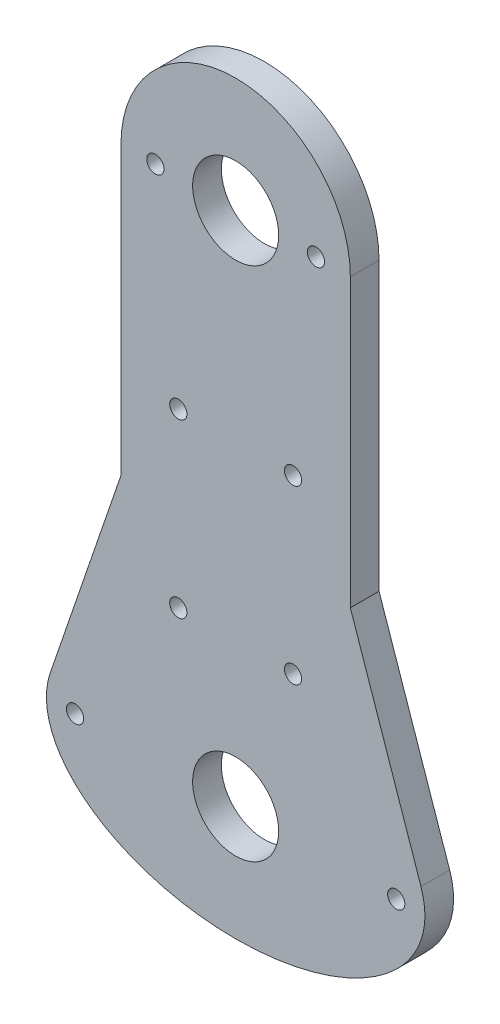
SolidWorks part; units mm, degrees
ref_plane "前视基准面" through (0, 0, 0) normal (0, 0, 1) x (1, 0, 0)
ref_plane "上视基准面" through (0, 0, 0) normal (0, 1, 0) x (1, 0, 0)
ref_plane "右视基准面" through (0, 0, 0) normal (1, 0, 0) x (0, 0, -1)
sketch "草图1" plane through (0, 0, 0) normal (0, 0, 1) x (1, 0, 0)
  line L0 (-20, -50) -> (-32.3109, -85.934)
  line L1 (-20, 0) -> (20, 0)
  line L2 (-20, 0) -> (-20, -90)
  line L3 (-20, -90) -> (20, -90)
  line L4 (20, 0) -> (20, -90)
  line L5 (-20, -50) -> (20, -50) construction
  line L6 (0, -50) -> (0, -154.1436) construction
  line L7 (20, -50) -> (32.3109, -85.934)
  circle A0 centre (0, 0) radius 20
  circle A1 centre (0, -90) radius 20
  ellipse E0 centre (0, -90) end of major axis (-33, -90) minor radius 20
  point P19 (0, 0)
  dimension "D1" = 40
  dimension "D2" = 90
  dimension "D3" = 40
  dimension "D4" = 33
extrude "凸台-拉伸1" add sketch "草图1" along normal blind 5 contours E0 L4 A0 L2 | E0 L2 L0 | L2 E0 A1 | A1 E0 L2 | L4 E0 A1 | E0 L7 L4 | E0 L4 A1 | L1 A0 | L1 A0 | L3 A1 | L3 A1
sketch "草图3" plane through (0, 0, 5) normal (0, 0, 1) x (1, 0, 0)
  line L4 (32.3109, -85.934) -> (20, -50)
  line L5 (20, -50) -> (20, 0)
  line L6 (-20, 0) -> (-20, -50)
  line L7 (-20, -50) -> (-32.3109, -85.934)
  line L8 (32.3109, -85.934) -> (20, -50)
  line L9 (20, -50) -> (20, 0)
  line L10 (-20, 0) -> (-20, -50)
  line L11 (-20, -50) -> (-32.3109, -85.934)
  circle A0 centre (0, -90) radius 7.5
  arc A1 (20, 0) -> (-20, 0) centre (0, 0) ccw
  arc A2 (20, 0) -> (-20, 0) centre (0, 0) ccw
  ellipse E1 centre (0, -90) end of major axis (-33, -90) minor radius 20 (-32.3109, -85.934) -> (32.3109, -85.934) ccw
  ellipse E2 centre (0, -90) end of major axis (-33, -90) minor radius 20 (-32.3109, -85.934) -> (32.3109, -85.934) ccw
  dimension "D2" = 15
  dimension "D1" = 0
extrude "切除-拉伸2" cut sketch "草图3" against normal through all both and the other way through all flip side to cut
sketch "草图4" plane through (0, 0, 5) normal (0, 0, 1) x (1, 0, 0)
  circle A0 centre (0, 0) radius 7.5
  dimension "D1" = 15
extrude "切除-拉伸3" cut sketch "草图4" against normal through all
sketch "草图5" plane through (0, 0, 5) normal (0, 0, 1) x (1, 0, 0)
  line L0 (0, -90) -> (33, -90) construction
  line L1 (0, -70) -> (0, -90) construction
  line L2 (0, 0) -> (0, -70) construction
  line L3 (0, -35) -> (20, -35) construction
  line L4 (32.3109, -85.934) -> (20, -50)
  line L5 (20, -50) -> (20, 0)
  line L6 (-20, 0) -> (-20, -50)
  line L7 (-20, -50) -> (-32.3109, -85.934)
  line L8 (32.3109, -85.934) -> (20, -50) construction
  line L9 (20, -50) -> (20, 0) construction
  line L10 (-20, 0) -> (-20, -50) construction
  line L11 (-20, -50) -> (-32.3109, -85.934) construction
  line L12 (10, -35) -> (10, -65) construction
  line L13 (10, -35) -> (10, 0) construction
  line L14 (10, -17.5) -> (0, -17.5) construction
  line L15 (10, 0) -> (14, 0) construction
  line L16 (0, -90) -> (0, -97.5) construction
  line L17 (0, -97.5) -> (0, -110) construction
  circle A0 centre (28, -90) radius 1.5
  arc A1 (20, 0) -> (-20, 0) centre (0, 0) ccw
  arc A2 (20, 0) -> (-20, 0) centre (0, 0) ccw construction
  circle A3 centre (14, 0) radius 1.5
  circle A5 centre (10, -35) radius 1.5
  circle A6 centre (10, -65) radius 1.5
  circle A7 centre (-14, 0) radius 1.5
  circle A8 centre (-10, -35) radius 1.5
  circle A9 centre (-10, -65) radius 1.5
  circle A10 centre (-28, -90) radius 1.5
  circle A11 centre (0, -90) radius 7.5 construction
  ellipse E1 centre (0, -90) end of major axis (-33, -90) minor radius 20 (-32.3109, -85.934) -> (32.3109, -85.934) ccw
  ellipse E2 centre (0, -90) end of major axis (-33, -90) minor radius 20 (-32.3109, -85.934) -> (32.3109, -85.934) ccw construction
  dimension "D3" = 3
  dimension "D6" = 3
  dimension "D7" = 3
  dimension "D8" = 3
  dimension "D2" = 5
  dimension "D4" = 30
  dimension "D5" = 4
  dimension "D1" = 0
extrude "切除-拉伸4" cut sketch "草图5" against normal up to surface (5 mm away) up to face at (7.5, 0, 0)
